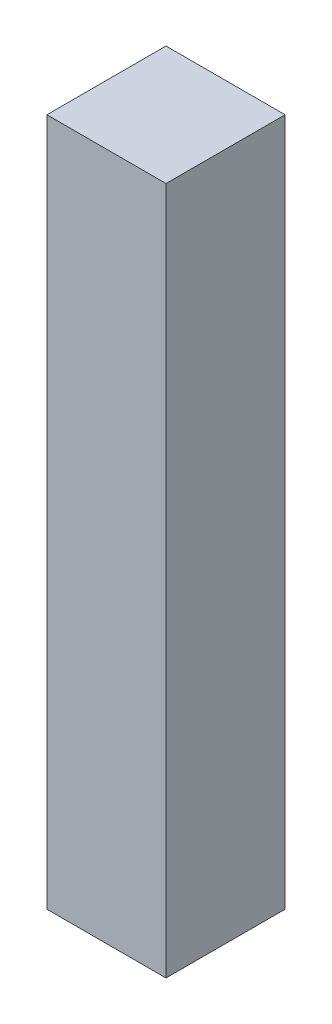
SolidWorks part; units mm, degrees
ref_plane "Front Plane" through (0, 0, 0) normal (0, 0, 1) x (1, 0, 0)
ref_plane "Top Plane" through (0, 0, 0) normal (0, 1, 0) x (1, 0, 0)
ref_plane "Right Plane" through (0, 0, 0) normal (1, 0, 0) x (0, 0, -1)
sketch "Sketch1" plane through (0, 0, 0) normal (0, 1, 0) x (1, 0, 0)
  line L1 (-57.15, -57.15) -> (57.15, -57.15)
  line L2 (-57.15, -57.15) -> (-57.15, 57.15)
  line L3 (-57.15, 57.15) -> (57.15, 57.15)
  line L4 (57.15, -57.15) -> (57.15, 57.15)
  line L5 (-57.15, -57.15) -> (57.15, 57.15) construction
  line L6 (-57.15, 57.15) -> (57.15, -57.15) construction
  point P0 (0, 0)
  dimension "D1" = 114.3
  dimension "D2" = 114.3
extrude "Boss-Extrude1" add sketch "Sketch1" along normal blind 660.4
sketch "Sketch2" plane through (0, 0, 0) normal (0, 1, 0) x (1, 0, 0)
  circle A0 centre (0, 0) radius 3.9688
  dimension "D1" = 7.9375
extrude "Cut-Extrude1" cut sketch "Sketch2" along normal blind 25.4
